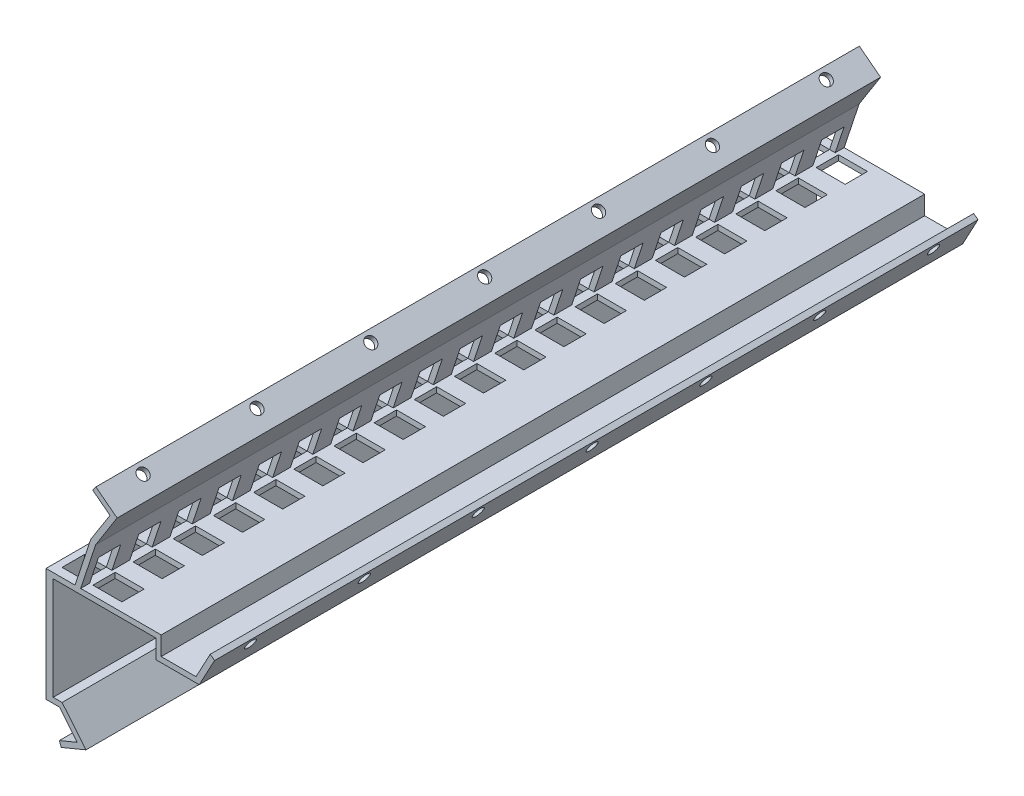
SolidWorks part; units mm, degrees
ref_plane "Front Plane" through (0, 0, 0) normal (0, 0, 1) x (1, 0, 0)
ref_plane "Top Plane" through (0, 0, 0) normal (0, 1, 0) x (1, 0, 0)
ref_plane "Right Plane" through (0, 0, 0) normal (1, 0, 0) x (0, 0, -1)
sketch "Sketch1" plane through (0, 0, 0) normal (0, 0, 1) x (1, 0, 0)
  line L0 (0, 0) -> (2, 0)
  line L1 (0, 0) -> (0, 23)
  line L2 (0, 23) -> (23, 23)
  line L6 (24.2, 24.2) -> (6.164, 24.2)
  line L7 (6.164, 24.2) -> (9.5163, 34.3338)
  line L9 (8.4234, 34.8509) -> (4.9, 24.2)
  line L10 (4.9, 24.2) -> (-1.6, 24.2)
  line L11 (-1.6, 24.2) -> (-1.6, -1.2)
  line L12 (-1.6, -1.2) -> (1.4329, -1.2)
  line L14 (23, 23) -> (23, 18.8)
  line L15 (23, 18.8) -> (32.7151, 18.8)
  line L16 (24.2, 24.2) -> (24.2, 20)
  line L17 (24.2, 20) -> (31.9971, 20)
  line L18 (31.9971, 20) -> (35.1828, 25.9373)
  line L20 (36.1475, 25.1971) -> (32.7151, 18.8)
  line L25 (53.9979, 11.5) -> (8.753, 46.2177) construction
  line L26 (53.9979, 11.5) -> (1.3091, -10.3244) construction
  line L31 (35.1828, 25.9373) -> (36.1475, 25.1971)
  line L35 (14.1924, 40.5313) -> (32.8248, 26.2341) construction
  line L36 (9.5163, 34.3338) -> (14.3303, 41.9381)
  line L37 (14.3303, 41.9381) -> (9.5702, 45.5906)
  line L38 (9.5702, 45.5906) -> (8.8396, 44.6386)
  line L39 (8.8396, 44.6386) -> (12.7299, 41.6535)
  line L40 (12.7299, 41.6535) -> (8.4234, 34.8509)
  line L41 (2, 0) -> (7.358, -6.52)
  line L48 (1.3898, -7.6933) -> (5.4029, -6.031)
  line L49 (5.4029, -6.031) -> (1.4329, -1.2)
  line L50 (1.3898, -7.6933) -> (1.8133, -8.8167)
  line L51 (1.8133, -8.8167) -> (7.358, -6.52)
  circle A0 centre (53.9979, 11.5) radius 57.03 construction
  circle A1 centre (53.9979, 11.5) radius 50 construction
  circle A2 centre (53.9979, 11.5) radius 22.5 construction
  circle A3 centre (53.9979, 11.5) radius 23.7159 construction
  circle A4 centre (53.9979, 11.5) radius 56 construction
  point P31 (10.5766, 38.2522)
  point P32 (1, 0)
  dimension "D21" = 114.06
  dimension "D14" = 100
  dimension "D8" = 45
  dimension "D1" = 2
  dimension "D2" = 23
  dimension "D3" = 23
  dimension "D4" = 1.2
  dimension "D5" = 1.2
  dimension "D6" = 1.6
  dimension "D7" = 1.2
  dimension "D9" = 6.5
  dimension "D10" = 4.2
  dimension "D11" = 1.2
  dimension "D12" = 1.2
  dimension "D13" = 1.2
  dimension "D15" = 1.2
  dimension "D16" = 6
  dimension "D17" = 1.2
  dimension "D18" = 9
  dimension "D19" = 1.2
  dimension "D20" = 1.2
  dimension "D22" = 60
  dimension "D23" = 22.5
  dimension "D24" = 1.2
  dimension "D25" = 1.2
  dimension "D26" = 4.3438
extrude "Boss-Extrude1" add sketch "Sketch1" along normal mid plane 171
sketch "Sketch2" plane through (-1.6, 0, 0) normal (-1, 0, 0) x (0, 0, 1)
  line L0 (81, 30.2) -> (81, 14.3801) construction
  line L1 (78.5, 21.2) -> (83.5, 21.2)
  line L2 (78.5, 21.2) -> (78.5, 30.2)
  line L3 (78.5, 30.2) -> (83.5, 30.2)
  line L4 (83.5, 21.2) -> (83.5, 30.2)
  line L5 (85.5, 24.2) -> (-85.5, 24.2) construction
  dimension "D1" = 4.5
  dimension "D2" = 5
  dimension "D3" = 3
  dimension "D4" = 9
extrude "Cut-Extrude1" cut sketch "Sketch2" against normal blind 15
pattern_linear "LPattern2" count 19 spacing 9 along (0, 0, -1) of "Cut-Extrude1"
sketch "Sketch3" plane through (2.9235, -7.058, 0) normal (-0.3827, 0.9239, 0) x (0.9239, 0.3827, 0)
  line L0 (2.6837, -85.5) -> (-1.6601, -85.5) construction
  line L1 (-1.6601, -85.5) -> (-1.6601, 85.5) construction
  circle A0 centre (0.3399, -76.5) radius 1.25
  dimension "D2" = 2
  dimension "D3" = 2.5
  dimension "D1" = 9
extrude "Cut-Extrude2" cut sketch "Sketch3" against normal blind 12
sketch "Sketch4" plane through (24.8347, 32.3652, 0) normal (-0.6088, -0.7934, 0) x (0.7934, -0.6088, 0)
  line L0 (-20.1613, 85.5) -> (-15.2578, 85.5) construction
  line L1 (-20.1613, 85.5) -> (-20.1613, -85.5) construction
  circle A0 centre (-18.1613, 76.5) radius 1.25
  dimension "D1" = 9
  dimension "D2" = 2
  dimension "D3" = 2.5
extrude "Cut-Extrude3" cut sketch "Sketch4" against normal blind 12
sketch "Sketch5" plane through (17.5697, -9.4271, 0) normal (0.8812, -0.4728, 0) x (0, 0, -1)
  line L0 (-85.5, 32.0336) -> (-85.5, 39.2934) construction
  line L1 (-85.5, 39.2934) -> (85.5, 39.2934) construction
  circle A0 centre (-76.5, 37.2934) radius 1.25
  dimension "D1" = 9
  dimension "D2" = 2.5
  dimension "D3" = 2
extrude "Cut-Extrude4" cut sketch "Sketch5" against normal blind 5
pattern_linear "LPattern3" count 7 spacing 25.5 along (0, 0, -1) of "Cut-Extrude2", "Cut-Extrude3", "Cut-Extrude4"
sketch "Sketch6" plane through (0, 0, 85.5) normal (0, 0, 1) x (1, 0, 0)
  line L1 (4.9, 24.2) -> (6.9, 24.2)
  line L2 (4.9, 24.2) -> (4.9, 23)
  line L3 (4.9, 23) -> (6.9, 23)
  line L4 (6.9, 24.2) -> (6.9, 23)
  line L5 (-1.6, 24.2) -> (0, 24.2)
  line L6 (-1.6, 24.2) -> (-1.6, 21.2)
  line L7 (-1.6, 21.2) -> (0, 21.2)
  line L8 (0, 24.2) -> (0, 21.2)
  line L10 (0, 23) -> (13.4, 23)
  line L11 (13.4, 23) -> (13.4, 24.2)
  line L12 (13.4, 24.2) -> (6.164, 24.2)
  line L13 (6.164, 24.2) -> (8.1488, 30.2)
  line L14 (8.1488, 30.2) -> (6.8848, 30.2)
  line L15 (6.8848, 30.2) -> (4.9, 24.2)
  line L16 (4.9, 24.2) -> (-1.6, 24.2)
  line L17 (-1.6, 24.2) -> (-1.6, 21.2)
  line L18 (-1.6, 21.2) -> (0, 21.2)
  line L19 (0, 21.2) -> (0, 23)
  line L20 (0, 23) -> (13.4, 23) construction
  line L21 (13.4, 23) -> (13.4, 24.2) construction
  line L22 (13.4, 24.2) -> (6.164, 24.2) construction
  line L23 (6.164, 24.2) -> (8.1488, 30.2) construction
  line L24 (8.1488, 30.2) -> (6.8848, 30.2) construction
  line L25 (6.8848, 30.2) -> (4.9, 24.2) construction
  line L26 (4.9, 24.2) -> (-1.6, 24.2) construction
  line L27 (-1.6, 24.2) -> (-1.6, 21.2) construction
  line L28 (-1.6, 21.2) -> (0, 21.2) construction
  line L29 (0, 21.2) -> (0, 23) construction
  dimension "D2" = 2
  dimension "D1" = 0
extrude "Boss-Extrude2" add sketch "Sketch6" against normal through all
